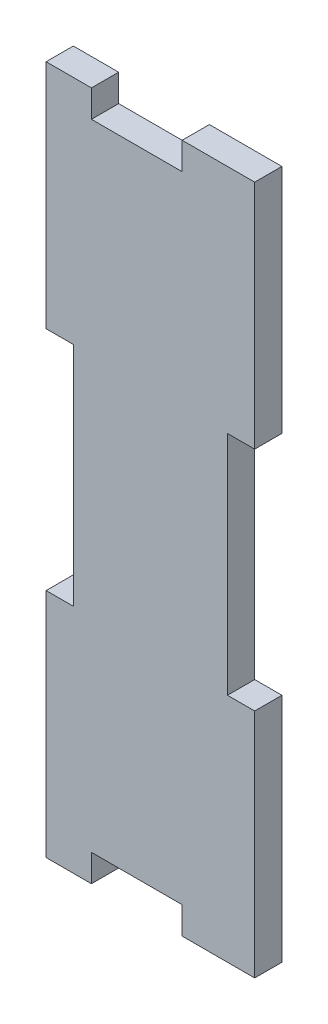
SolidWorks part; units mm, degrees
ref_plane "Front Plane" through (0, 0, 0) normal (0, 0, 1) x (1, 0, 0)
ref_plane "Top Plane" through (0, 0, 0) normal (0, 1, 0) x (1, 0, 0)
ref_plane "Right Plane" through (0, 0, 0) normal (1, 0, 0) x (0, 0, -1)
sketch "Sketch1" plane through (0, 0, 0) normal (0, 0, 1) x (1, 0, 0)
  line L0 (0, 76) -> (0, 50.5)
  line L1 (0, 25.5) -> (0, 0)
  line L2 (0, 50.5) -> (3, 50.5)
  line L4 (0, 25.5) -> (3, 25.5)
  line L5 (0, 0) -> (5, 0)
  line L6 (5, 0) -> (5, 3)
  line L7 (5, 3) -> (15, 3)
  line L8 (15, 3) -> (15, 0)
  line L9 (15, 0) -> (23, 0)
  line L10 (23, 0) -> (23, 25.5)
  line L11 (23, 25.5) -> (20, 25.5)
  line L12 (20, 25.5) -> (20, 50.5)
  line L13 (20, 50.5) -> (23, 50.5)
  line L14 (23, 50.5) -> (23, 76)
  line L15 (23, 76) -> (15, 76)
  line L16 (15, 76) -> (15, 73)
  line L17 (15, 73) -> (5, 73)
  line L18 (5, 73) -> (5, 76)
  line L19 (5, 76) -> (0, 76)
  line L20 (3, 50.5) -> (3, 25.5)
  dimension "D1" = 23
  dimension "D2" = 3
  dimension "D3" = 10
  dimension "D4" = 76
  dimension "D5" = 25
  dimension "D6" = 5
extrude "Boss-Extrude1" add sketch "Sketch1" along normal blind 3
